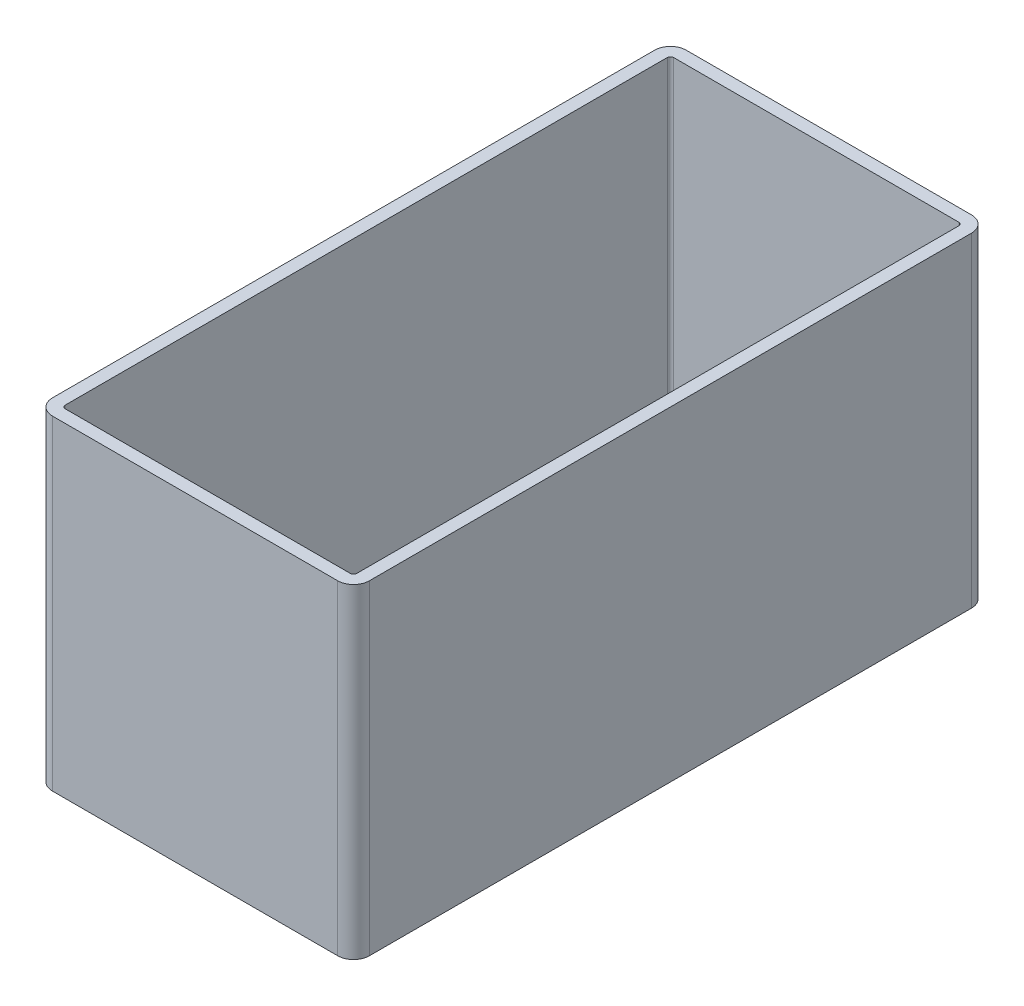
SolidWorks part; units mm, degrees
material "PC High Viscosity"
ref_plane "Front Plane" through (0, 0, 0) normal (0, 0, 1) x (1, 0, 0)
ref_plane "Top Plane" through (0, 0, 0) normal (0, 1, 0) x (1, 0, 0)
ref_plane "Right Plane" through (0, 0, 0) normal (1, 0, 0) x (0, 0, -1)
sketch "BaseS" plane through (0, 0, 0) normal (0, 1, 0) x (1, 0, 0)
  line L1 (-10, 20) -> (10, 20)
  line L2 (-10, 20) -> (-10, -20)
  line L3 (-10, -20) -> (10, -20)
  line L4 (10, 20) -> (10, -20)
  line L5 (-10, 20) -> (10, -20) construction
  line L6 (-10, -20) -> (10, 20) construction
  point P0 (0, 0)
  dimension "D1" = 20
  dimension "D2" = 40
extrude "BASE" add sketch "BaseS" along normal mid plane 20.5
fillet "BASE F" radius 1 4 edges at (-10, 0, -20) (10, 0, -20) (10, 0, 20) (-10, 0, 20)
sketch "PocketS" plane through (0, 10.25, 0) normal (0, 1, 0) x (1, 0, 0)
  line L0 (9, 19.2) -> (-9, 19.2)
  line L1 (-9.2, 19) -> (-9.2, -19)
  line L2 (-9, -19.2) -> (9, -19.2)
  line L3 (9.2, -19) -> (9.2, 19)
  line L4 (9, 20) -> (-9, 20)
  line L5 (-10, 19) -> (-10, -19)
  line L6 (-9, -20) -> (9, -20)
  line L7 (10, -19) -> (10, 19)
  line L8 (9, 20) -> (-9, 20) construction
  line L9 (-10, 19) -> (-10, -19) construction
  line L10 (-9, -20) -> (9, -20) construction
  line L11 (10, -19) -> (10, 19) construction
  arc A0 (-9, 19.2) -> (-9.2, 19) centre (-9, 19) ccw
  arc A1 (-9.2, -19) -> (-9, -19.2) centre (-9, -19) ccw
  arc A2 (9, -19.2) -> (9.2, -19) centre (9, -19) ccw
  arc A3 (9.2, 19) -> (9, 19.2) centre (9, 19) ccw
  arc A4 (-9, 20) -> (-10, 19) centre (-9, 19) ccw
  arc A5 (-10, -19) -> (-9, -20) centre (-9, -19) ccw
  arc A6 (9, -20) -> (10, -19) centre (9, -19) ccw
  arc A7 (10, 19) -> (9, 20) centre (9, 19) ccw
  arc A8 (-9, 20) -> (-10, 19) centre (-9, 19) ccw construction
  arc A9 (-10, -19) -> (-9, -20) centre (-9, -19) ccw construction
  arc A10 (9, -20) -> (10, -19) centre (9, -19) ccw construction
  arc A11 (10, 19) -> (9, 20) centre (9, 19) ccw construction
  dimension "D1" = 0
  dimension "D2" = 0.8
extrude "Cut-Extrude3" cut sketch "PocketS" against normal through all
equation "\"éà\"=19.8"
